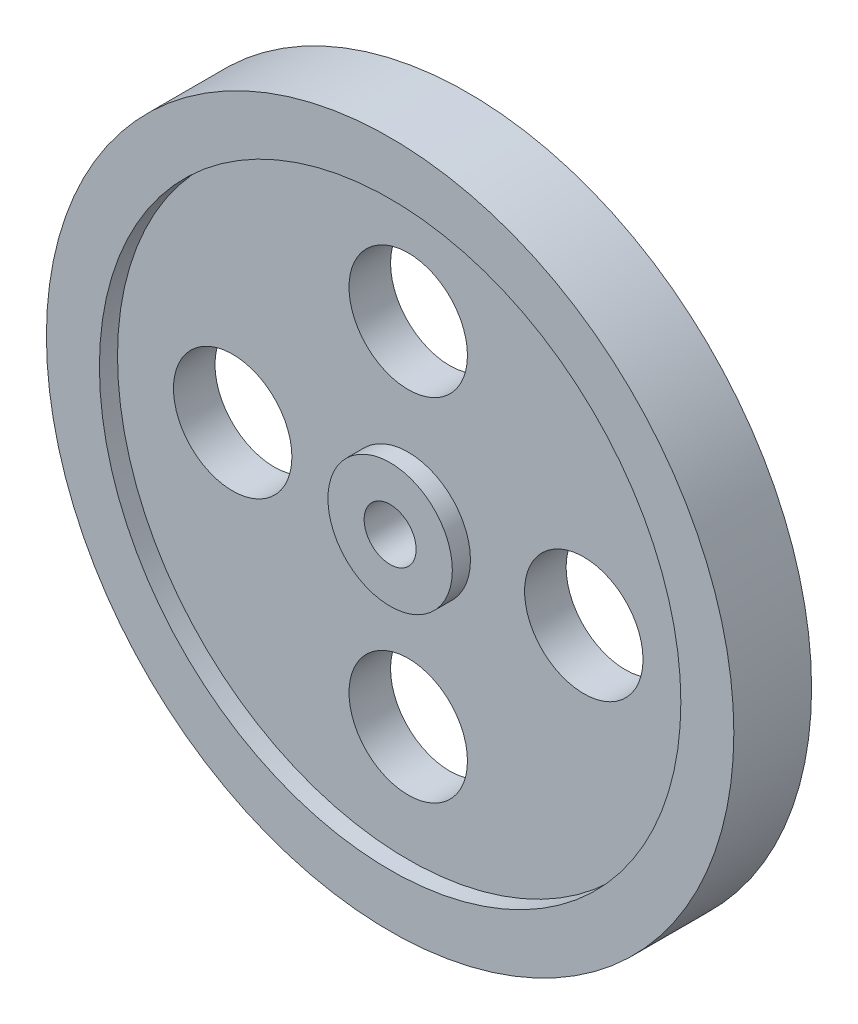
SolidWorks part; units mm, degrees
ref_plane "Front Plane" through (0, 0, 0) normal (0, 0, 1) x (1, 0, 0)
ref_plane "Top Plane" through (0, 0, 0) normal (0, 1, 0) x (1, 0, 0)
ref_plane "Right Plane" through (0, 0, 0) normal (1, 0, 0) x (0, 0, -1)
sketch "Sketch1" plane through (0, 0, 0) normal (0, 0, 1) x (1, 0, 0)
  circle A0 centre (0, 0) radius 24.6683
  circle A1 centre (0, 0) radius 1.8669
  dimension "D1" = 49.3365
  dimension "D2" = 3.7338
extrude "Boss-Extrude1" add sketch "Sketch1" along normal mid plane 5.58
sketch "Sketch2" plane through (0, 0, 2.79) normal (0, 0, 1) x (1, 0, 0)
  circle A0 centre (0, 0) radius 20.865
  circle A1 centre (0, 0) radius 4.465
  dimension "D1" = 41.73
  dimension "D2" = 8.93
extrude "Cut-Extrude1" cut sketch "Sketch2" against normal blind 1.3
sketch "Sketch3" plane through (0, 0, 1.49) normal (0, 0, 1) x (1, 0, 0)
  circle A0 centre (0, 12.6) radius 4.25
  circle A1 centre (12.6, 0) radius 4.25
  circle A2 centre (0, 0) radius 20.865 construction
  circle A3 centre (0, -12.6) radius 4.25
  circle A4 centre (-12.6, 0) radius 4.25
  point P13 (0, 0)
  dimension "D1" = 8.5
  dimension "D2" = 12.6
  dimension "D3" = 4
extrude "Cut-Extrude2" cut sketch "Sketch3" against normal through all
mirror "Mirror1" about plane through (0, 0, 0) normal (0, 0, 1) of "Cut-Extrude1"
